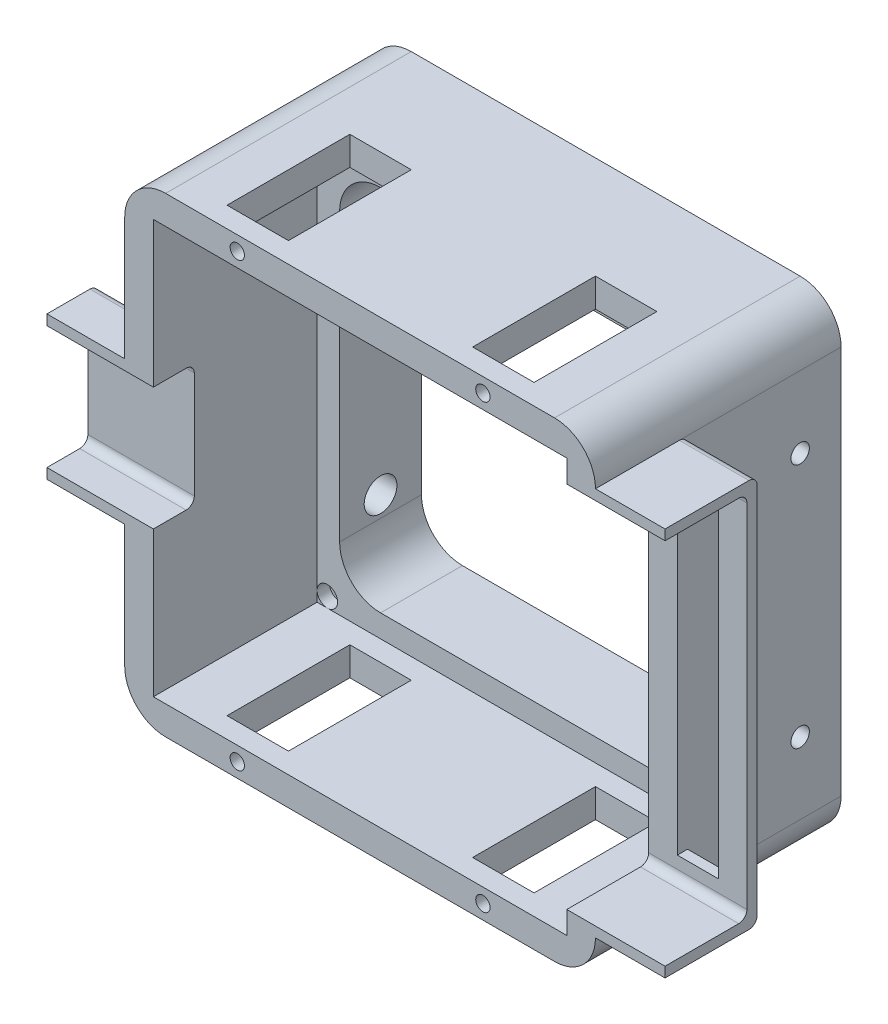
SolidWorks part; units mm, degrees
ref_plane "Front Plane" through (0, 0, 0) normal (0, 0, 1) x (1, 0, 0)
ref_plane "Top Plane" through (0, 0, 0) normal (0, 1, 0) x (1, 0, 0)
ref_plane "Right Plane" through (0, 0, 0) normal (1, 0, 0) x (0, 0, -1)
sketch "Sketch1" plane through (0, 0, 0) normal (0, 0, 1) x (1, 0, 0)
  line L1 (57.5, -57.5) -> (-57.5, -57.5)
  line L2 (57.5, -57.5) -> (57.5, 57.5)
  line L3 (57.5, 57.5) -> (-57.5, 57.5)
  line L4 (-57.5, -57.5) -> (-57.5, 57.5)
  line L5 (57.5, -57.5) -> (-57.5, 57.5) construction
  line L6 (57.5, 57.5) -> (-57.5, -57.5) construction
  point P0 (0, 0)
  dimension "D1" = 115
  dimension "D2" = 115
extrude "Boss-Extrude1" add sketch "Sketch1" along normal mid plane 80
fillet "Fillet1" radius 10 4 edges at (-57.5, -57.5, 0) (57.5, -57.5, 0) (57.5, 57.5, 0) (-57.5, 57.5, 0)
ref_plane "Plane1" through (0, 0, 40) normal (0, 0, 1) x (1, 0, 0)
sketch "Sketch4" plane through (0, 0, 40) normal (0, 0, 1) x (1, 0, 0)
  line L1 (50.5, -50.5) -> (-50.5, -50.5)
  line L2 (50.5, -50.5) -> (50.5, 50.5)
  line L3 (50.5, 50.5) -> (-50.5, 50.5)
  line L4 (-50.5, -50.5) -> (-50.5, 50.5)
  line L5 (50.5, -50.5) -> (-50.5, 50.5) construction
  line L6 (50.5, 50.5) -> (-50.5, -50.5) construction
  point P0 (0, 0)
  dimension "D1" = 101
  dimension "D2" = 101
extrude "Cut-Extrude3" cut sketch "Sketch4" against normal blind 40
ref_plane "Plane2" through (0, 0, -40) normal (0, 0, -1) x (-1, 0, 0)
ref_plane "Plane3" through (0, 0, 0) normal (0, 0, 1) x (1, 0, 0)
sketch "Sketch7" plane through (0, 0, 0) normal (0, 0, 1) x (1, 0, 0)
  line L1 (45, -45) -> (-45, -45)
  line L2 (45, -45) -> (45, 45)
  line L3 (45, 45) -> (-45, 45)
  line L4 (-45, -45) -> (-45, 45)
  line L5 (45, -45) -> (-45, 45) construction
  line L6 (45, 45) -> (-45, -45) construction
  point P0 (0, 0)
  dimension "D1" = 90
  dimension "D2" = 90
extrude "Cut-Extrude5" cut sketch "Sketch7" against normal blind 60
fillet "Fillet3" radius 10 4 edges at (-45, -45, -20) (45, -45, -20) (-45, 45, -20) (45, 45, -20)
sketch "Sketch8" plane through (0, 0, -40) normal (0, 0, -1) x (-1, 0, 0)
  circle A0 centre (-48, 48) radius 3.15
  dimension "D1" = 6.3
  dimension "D2" = 48
  dimension "D3" = 48
extrude "Cut-Extrude6" cut sketch "Sketch8" against normal blind 35
mirror "Mirror2" about plane through (0, 0, 0) normal (0, 1, 0) of "Cut-Extrude6" second plane through (0, 0, 0) second plane normal (1, 0, 0)
sketch "Sketch9" plane through (0, 0, 0) normal (0, 0, 1) x (1, 0, 0)
  circle A0 centre (-48, 48) radius 1.25
  dimension "D1" = 2.5
  dimension "D2" = 48
  dimension "D3" = 48
extrude "Cut-Extrude7" cut sketch "Sketch9" against normal blind 15
mirror "Mirror3" about plane through (0, 0, 0) normal (0, 1, 0) of "Cut-Extrude7" second plane through (0, 0, 0) second plane normal (1, 0, 0)
sketch "Sketch10" plane through (0, 0, 0) normal (0, 0, 1) x (1, 0, 0)
  circle A0 centre (-48, 48) radius 2.5
  dimension "D1" = 5
extrude "Cut-Extrude8" cut sketch "Sketch10" against normal blind 3
mirror "Mirror4" about plane through (0, 0, 0) normal (0, 1, 0) of "Cut-Extrude8" second plane through (0, 0, 0) second plane normal (1, 0, 0)
ref_plane "Plane4" through (57.5, 0, 0) normal (1, 0, 0) x (0, 0, -1)
sketch "Sketch11" plane through (57.5, 0, 0) normal (1, 0, 0) x (0, 0, -1)
  line L0 (-40, 23.375) -> (-40, -23.375) construction
  line L1 (-60, -45) -> (-20, -45)
  line L2 (-60, -45) -> (-60, 45)
  line L3 (-60, 45) -> (-20, 45)
  line L4 (-20, -45) -> (-20, 45)
  line L5 (-60, -45) -> (-20, 45) construction
  line L6 (-60, 45) -> (-20, -45) construction
  point P0 (-40, 0)
  dimension "D1" = 90
  dimension "D2" = 40
extrude "Cut-Extrude9" cut sketch "Sketch11" against normal blind 11
sketch "Sketch13" plane through (57.5, 0, 0) normal (1, 0, 0) x (0, 0, -1)
  line L0 (-40, 23.375) -> (-40, -23.375) construction
  line L1 (-20, 45) -> (-17.5, 45)
  line L2 (-20, 45) -> (-20, -45)
  line L3 (-20, -45) -> (-17.5, -45)
  line L4 (-17.5, 45) -> (-17.5, -45)
  line L5 (-17.5, 45) -> (-40, 45)
  line L6 (-17.5, 45) -> (-17.5, 47.5)
  line L7 (-17.5, 47.5) -> (-40, 47.5)
  line L8 (-40, 45) -> (-40, 47.5)
  line L9 (40, 47.5) -> (-40, 47.5) construction
  line L10 (-40, -47.5) -> (40, -47.5) construction
  line L11 (-17.5, -45) -> (-40, -45)
  line L12 (-17.5, -45) -> (-17.5, -47.5)
  line L13 (-17.5, -47.5) -> (-40, -47.5)
  line L14 (-40, -45) -> (-40, -47.5)
  dimension "D1" = 90
  dimension "D2" = 2.5
extrude "Boss-Extrude2" add sketch "Sketch13" along normal blind 17 contours L4 L1 L2 L3 | L11 L14 L13 L12 L3 | L8 L5 L1 L6 L7
fillet "Fillet6" radius 2 4 edges at (62.5, -45, 20) (66, -47.5, 17.5) (62.5, 45, 20) (66, 47.5, 17.5)
ref_plane "Plane5" through (-57.5, 0, 0) normal (-1, 0, 0) x (0, 0, 1)
sketch "Sketch14" plane through (-57.5, 0, 0) normal (-1, 0, 0) x (0, 0, 1)
  line L0 (40, 47.5) -> (40, -47.5) construction
  line L1 (50, -15) -> (30, -15)
  line L2 (50, -15) -> (50, 15)
  line L3 (50, 15) -> (30, 15)
  line L4 (30, -15) -> (30, 15)
  line L5 (50, -15) -> (30, 15) construction
  line L6 (50, 15) -> (30, -15) construction
  point P0 (40, 0)
  dimension "D1" = 30
  dimension "D2" = 20
extrude "Cut-Extrude10" cut sketch "Sketch14" against normal blind 11
sketch "Sketch15" plane through (-57.5, 0, 0) normal (-1, 0, 0) x (0, 0, 1)
  line L0 (40, -23.375) -> (40, 23.375) construction
  line L1 (30, 15) -> (40, 15)
  line L2 (30, 15) -> (30, 17.5)
  line L3 (30, 17.5) -> (40, 17.5)
  line L4 (40, 15) -> (40, 17.5)
  line L5 (40, -15) -> (40, -47.5) construction
  line L6 (30, -15) -> (40, -15)
  line L7 (30, -15) -> (30, -17.5)
  line L8 (30, -17.5) -> (40, -17.5)
  line L9 (40, -15) -> (40, -17.5)
  line L11 (30, 17.5) -> (27.5, 17.5)
  line L12 (30, 17.5) -> (30, -17.5)
  line L13 (30, -17.5) -> (27.5, -17.5)
  line L14 (27.5, 17.5) -> (27.5, -17.5)
  dimension "D1" = 2.5
  dimension "D2" = 2.5
  dimension "D3" = 2.5
extrude "Boss-Extrude3" add sketch "Sketch15" along normal blind 19 contours L11 L14 L13 L7 L12 L2 | L1 L4 L3 L2 | L9 L6 L7 L8
fillet "Fillet7" radius 2 4 edges at (-63.5, -15, 30) (-63.5, 15, 30) (-67, -17.5, 27.5) (-67, 17.5, 27.5)
ref_plane "Plane6" through (0, 0, -40) normal (0, 0, -1) x (-1, 0, 0)
sketch "Sketch16" plane through (0, 0, -40) normal (0, 0, -1) x (-1, 0, 0)
  line L0 (-57.5, 31.35) -> (-57.5, -31.35) construction
  line L1 (57.5, -57.5) -> (-57.5, -57.5)
  line L2 (57.5, -57.5) -> (57.5, 57.5)
  line L3 (57.5, 57.5) -> (-57.5, 57.5)
  line L4 (-57.5, -57.5) -> (-57.5, 57.5)
  line L5 (57.5, -57.5) -> (-57.5, 57.5) construction
  line L6 (57.5, 57.5) -> (-57.5, -57.5) construction
  point P0 (0, 0)
  dimension "D1" = 115
extrude "Cut-Extrude12" cut sketch "Sketch16" against normal blind 20
ref_plane "Plane7" through (0, 0, 17.5) normal (0, 0, -1) x (-1, 0, 0)
sketch "Sketch17" plane through (0, 0, 17.5) normal (0, 0, -1) x (-1, 0, 0)
  line L1 (-57.5, -40) -> (-67.5, -40)
  line L2 (-57.5, -40) -> (-57.5, 40)
  line L3 (-57.5, 40) -> (-67.5, 40)
  line L4 (-67.5, -40) -> (-67.5, 40)
  line L5 (-57.5, -40) -> (-67.5, 40) construction
  line L6 (-57.5, 40) -> (-67.5, -40) construction
  point P0 (-62.5, 0)
  dimension "D1" = 62.5
  dimension "D2" = 10
  dimension "D3" = 80
extrude "Cut-Extrude13" cut sketch "Sketch17" against normal blind 15
sketch "Sketch20" plane through (57.5, 0, 0) normal (1, 0, 0) x (0, 0, -1)
  circle A1 centre (10, 30) radius 2.25
  dimension "D1" = 4.5
  dimension "D2" = 30
  dimension "D3" = 10
extrude "Cut-Extrude14" cut sketch "Sketch20" against normal blind 25
mirror "Mirror8" about plane through (0, 0, 0) normal (1, 0, 0) of "Cut-Extrude14" second plane through (0, 0, 0) second plane normal (0, 1, 0)
sketch "Sketch21" plane through (0, 0, 40) normal (0, 0, 1) x (1, 0, 0)
  circle A1 centre (30, 54) radius 1.75
  dimension "D1" = 3.5
  dimension "D2" = 30
  dimension "D3" = 54
extrude "Cut-Extrude15" cut sketch "Sketch21" against normal blind 20
mirror "Mirror9" about plane through (0, 0, 0) normal (0, 1, 0) of "Cut-Extrude15" second plane through (0, 0, 0) second plane normal (1, 0, 0)
ref_plane "Plane8" through (0, 57.5, 0) normal (0, 1, 0) x (1, 0, 0)
sketch "Sketch24" plane through (0, 57.5, 0) normal (0, 1, 0) x (1, 0, 0)
  line L5 (22.5, -5) -> (37.5, -5)
  line L6 (22.5, -5) -> (22.5, -35)
  line L7 (22.5, -35) -> (37.5, -35)
  line L8 (37.5, -5) -> (37.5, -35)
  line L9 (22.5, -5) -> (37.5, -35) construction
  line L10 (22.5, -35) -> (37.5, -5) construction
  point P0 (30, -20)
  dimension "D1" = 30
  dimension "D2" = 30
  dimension "D3" = 20
  dimension "D4" = 15
extrude "Cut-Extrude16" cut sketch "Sketch24" against normal blind 10
mirror "Mirror10" about plane through (0, 0, 0) normal (1, 0, 0) of "Cut-Extrude16" second plane through (0, 0, 0) second plane normal (0, 1, 0)
ref_plane "Plane9" through (45, 0, 0) normal (-1, 0, 0) x (0, 0, 1)
sketch "Sketch25" plane through (45, 0, 0) normal (-1, 0, 0) x (0, 0, 1)
  circle A0 centre (-10, 30) radius 4
  dimension "D1" = 8
extrude "Cut-Extrude17" cut sketch "Sketch25" against normal blind 7.5
mirror "Mirror11" about plane through (0, 0, 0) normal (0, 1, 0) of "Cut-Extrude17" second plane through (0, 0, 0) second plane normal (1, 0, 0)
ref_plane "Plane10" through (0, 0, -5) normal (0, 0, 1) x (1, 0, 0)
sketch "Sketch26" plane through (0, 0, -5) normal (0, 0, 1) x (1, 0, 0)
  line L0 (-35, 45) -> (-35, 50.5)
  line L1 (50.5, 50.5) -> (48, 50.5) construction
  line L2 (-35, 50.5) -> (-50.5, 50.5)
  line L3 (-50.5, 50.5) -> (-50.5, 35)
  line L4 (-50.5, 50.5) -> (-50.5, 15) construction
  line L5 (-50.5, 35) -> (-45, 35)
  arc A0 (-45, 35) -> (-35, 45) centre (-35, 35) cw
extrude "Cut-Extrude18" [suppressed] cut sketch "Sketch26" against normal blind 5
